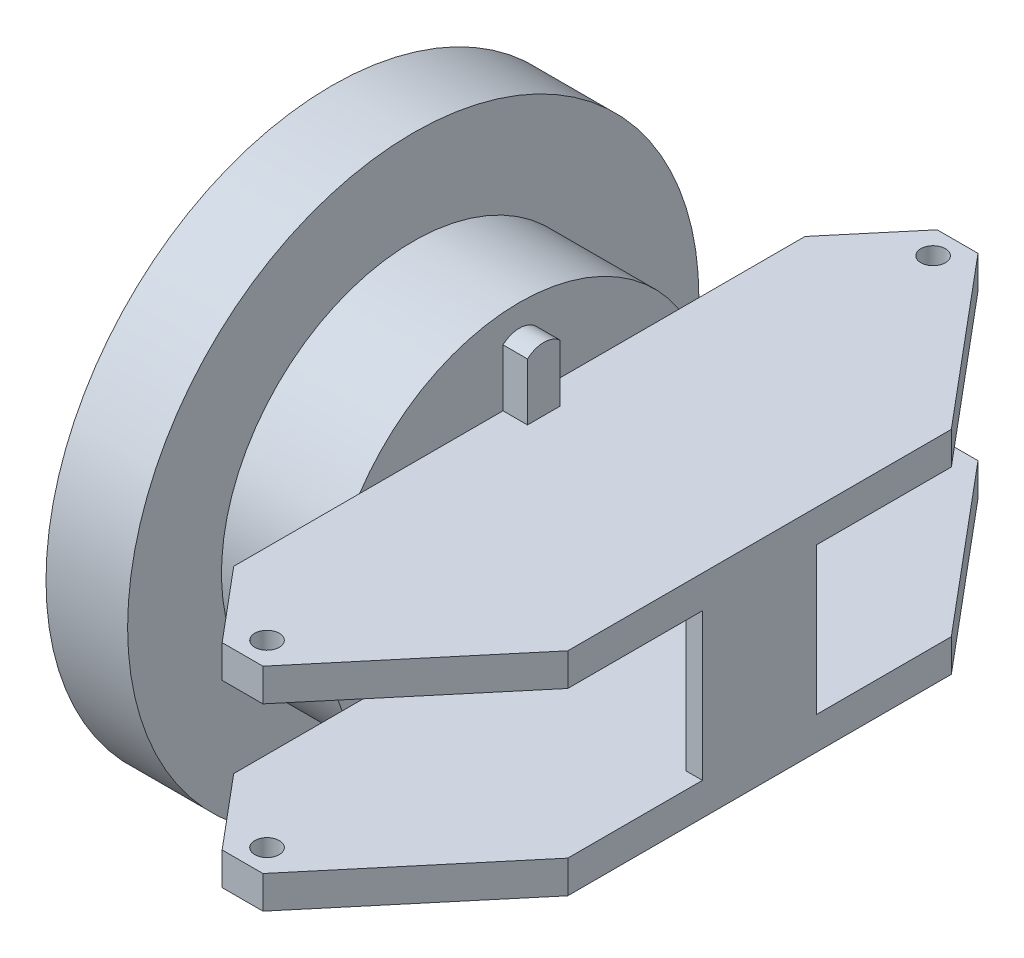
SolidWorks part; units mm, degrees
ref_plane "Front Plane" through (0, 0, 0) normal (0, 0, 1) x (1, 0, 0)
ref_plane "Top Plane" through (0, 0, 0) normal (0, 1, 0) x (1, 0, 0)
ref_plane "Right Plane" through (0, 0, 0) normal (1, 0, 0) x (0, 0, -1)
sketch "Sketch1" plane through (0, 0, 0) normal (1, 0, 0) x (0, 0, -1)
  line L0 (136.2441, 210.8334) -> (489.5014, 210.8334) construction
  circle A0 centre (0, 0) radius 35
  dimension "D1" = 70
extrude "Boss-Extrude1" add sketch "Sketch1" along normal blind 10
sketch "Sketch2" plane through (10, 0, 0) normal (1, 0, 0) x (0, 0, -1)
  circle A0 centre (0, 0) radius 23.5
  dimension "D1" = 47
extrude "Boss-Extrude2" add sketch "Sketch2" along normal blind 13
ref_plane "Plane1" through (0, 13, 0) normal (0, 1, 0) x (1, 0, 0)
sketch "Sketch3" plane through (0, 13, 0) normal (0, 1, 0) x (1, 0, 0)
  line L0 (23, 35) -> (23, -35)
  line L1 (23, -23.5) -> (23, 23.5) construction
  line L2 (23, -35) -> (30.3921, -43.8095)
  line L3 (30.3921, -43.8095) -> (35.3921, -43.8095)
  line L4 (35.3921, -43.8095) -> (52.4338, -23.5)
  line L5 (52.4338, -23.5) -> (52.4338, 23.5)
  line L6 (23, -23.5) -> (69.7796, -23.5) construction
  line L7 (10, -23.5) -> (23, -23.5) construction
  line L8 (23, 0) -> (86.2059, 0) construction
  line L9 (35.3921, 43.8095) -> (52.4338, 23.5)
  line L10 (30.3921, 43.8095) -> (35.3921, 43.8095)
  line L11 (23, 35) -> (30.3921, 43.8095)
  point P14 (52.4338, 0)
  dimension "D1" = 35
  dimension "D2" = 11.5
  dimension "D3" = 5
  dimension "D4" = 40
  dimension "D5" = 50
extrude "Boss-Extrude3" add sketch "Sketch3" against normal blind 4
sketch "Sketch4" plane through (0, 13, 0) normal (0, 1, 0) x (1, 0, 0)
  line L0 (30.3921, -43.8095) -> (35.3921, -43.8095) construction
  line L1 (32.8921, -43.8095) -> (32.8921, -37.4133) construction
  circle A0 centre (32.8921, -40.8095) radius 1.5
  dimension "D1" = 3
  dimension "D2" = 3
extrude "Cut-Extrude1" cut sketch "Sketch4" against normal blind 4
mirror "Mirror1" about plane through (0, 0, 0) normal (0, 0, 1) of "Cut-Extrude1"
mirror "Mirror2" about plane through (0, 0, 0) normal (0, 1, 0) of "Mirror1", "Cut-Extrude1", "Boss-Extrude3"
sketch "Sketch5" plane through (23, 0, 0) normal (1, 0, 0) x (0, 0, -1)
  line L0 (0, 13) -> (0, 23.5) construction
  line L1 (32.4759, 13) -> (-32.4759, 13) construction
  line L2 (-2, 13) -> (-2, 20)
  line L3 (-2, 13) -> (2, 13)
  line L4 (2, 13) -> (2, 20)
  arc A0 (19.5768, 13) -> (-19.5768, 13) centre (0, 0) ccw construction
  arc A1 (-2, 20) -> (2, 20) centre (0, 17.7639) cw
  dimension "D5" = 3
  dimension "D1" = 2
  dimension "D2" = 2
  dimension "D3" = 7
  dimension "D4" = 7
extrude "Boss-Extrude4" add sketch "Sketch5" along normal blind 3
mirror "Mirror3" about plane through (0, 0, 0) normal (0, 1, 0) of "Boss-Extrude4"
sketch "Sketch6" plane through (52.4338, 0, 0) normal (1, 0, 0) x (0, 0, -1)
  line L0 (19.5768, -13) -> (2, -13) construction
  line L1 (-7, 13) -> (7, 13)
  line L2 (-7, 13) -> (-7, -13)
  line L3 (-7, -13) -> (7, -13)
  line L4 (7, 13) -> (7, -13)
  line L5 (-7, 13) -> (7, -13) construction
  line L6 (-7, -13) -> (7, 13) construction
  point P0 (0, 0)
  dimension "D1" = 14
extrude "Boss-Extrude5" add sketch "Sketch6" against normal blind 2
sketch "Sketch7" plane through (0, 0, 0) normal (-1, 0, 0) x (0, 0, 1)
  circle A0 centre (0, 0) radius 10
  dimension "D1" = 20
extrude "Cut-Extrude2" cut sketch "Sketch7" against normal blind 10
